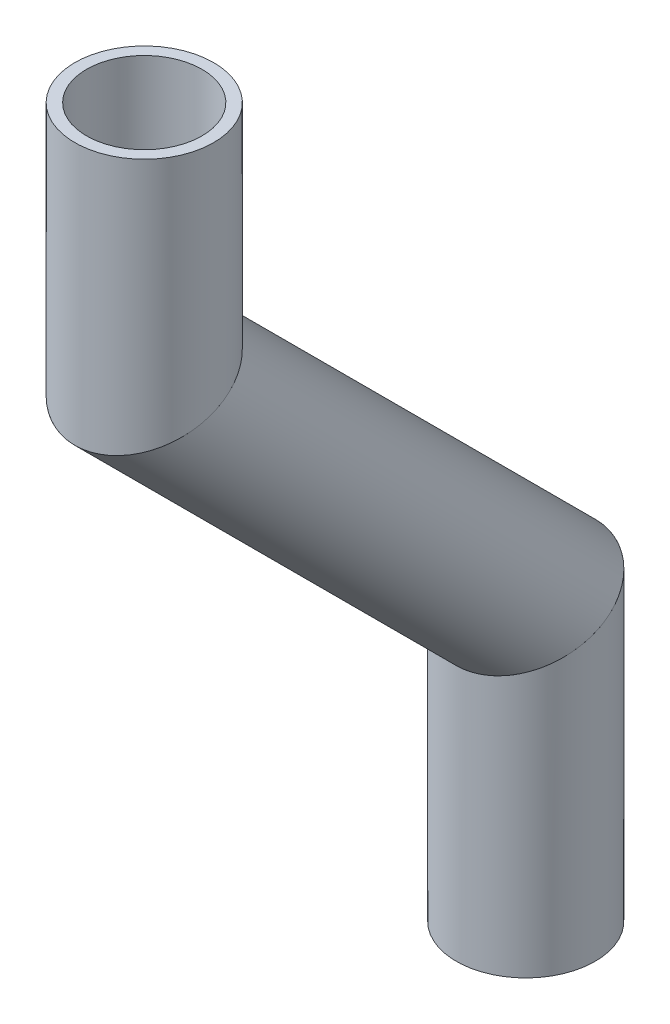
SolidWorks part; units mm, degrees
ref_plane "Front Plane" through (0, 0, 0) normal (0, 0, 1) x (1, 0, 0)
ref_plane "Top Plane" through (0, 0, 0) normal (0, 1, 0) x (1, 0, 0)
ref_plane "Right Plane" through (0, 0, 0) normal (1, 0, 0) x (0, 0, -1)
sketch "Sketch1" plane through (0, 0, 0) normal (1, 0, 0) x (0, 0, -1)
  line L0 (-362.7653, -435.3411) -> (-362.7653, -456.7019)
  line L1 (-362.7653, -456.7019) -> (-327.8546, -491.6126)
  line L2 (-327.8546, -491.6126) -> (-327.8546, -517.6817)
  line L3 (-362.7653, -456.7019) -> (-362.7653, -499.5396) construction
  dimension "D1" = 45
other "Pipe 0.5 SCH 40(1)"
ref_plane "Plane1" through (0, -435.3411, 362.7653) normal (0, -1, 0) x (0, 0, -1)
sketch "Sketch11" plane through (0, -435.3411, 362.7653) normal (0, -1, 0) x (0, 0, -1)
  circle A0 centre (0, 0) radius 5.2832
  circle A1 centre (0, 0) radius 6.35
  point P5 (0, 0)
  dimension "In_dia" = 10.5664
  dimension "Out_dia" = 12.7
